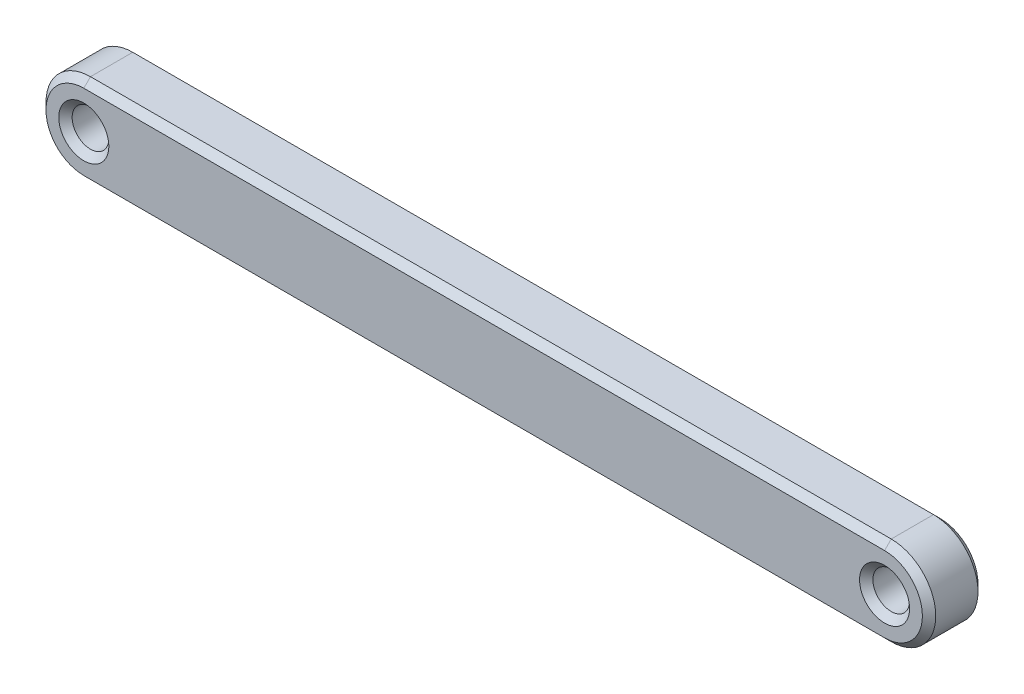
SolidWorks part; units mm, degrees
ref_plane "前视基准面" through (0, 0, 0) normal (0, 0, 1) x (1, 0, 0)
ref_plane "上视基准面" through (0, 0, 0) normal (0, 1, 0) x (1, 0, 0)
ref_plane "右视基准面" through (0, 0, 0) normal (1, 0, 0) x (0, 0, -1)
sketch "草图1" plane through (0, 0, 0) normal (0, 0, 1) x (1, 0, 0)
  line L0 (-36, 0) -> (36, 0) construction
  line L1 (-36, 4) -> (36, 4)
  line L2 (-36, -4) -> (36, -4)
  arc A0 (-36, 4) -> (-36, -4) centre (-36, 0) ccw
  arc A1 (36, -4) -> (36, 4) centre (36, 0) ccw
  circle A2 centre (-36, 0) radius 1.65
  circle A3 centre (36, 0) radius 1.65
  point P2 (0, 0)
  dimension "D2" = 4
  dimension "D3" = 3.3
  dimension "D4" = 3.3
  dimension "D1" = 72
extrude "凸台-拉伸1" add sketch "草图1" along normal blind 5
chamfer "倒角1" distance 0.6 angle 45 12 edges at (37.65, 0, 0) (-34.35, 0, 0) (37.65, 0, 5) (-34.35, 0, 5) (0, -4, 0) (40, 0, 0) (-40, 0, 0) (0, 4, 0) (0, -4, 5) (40, 0, 5) (-40, 0, 5) (0, 4, 5)
